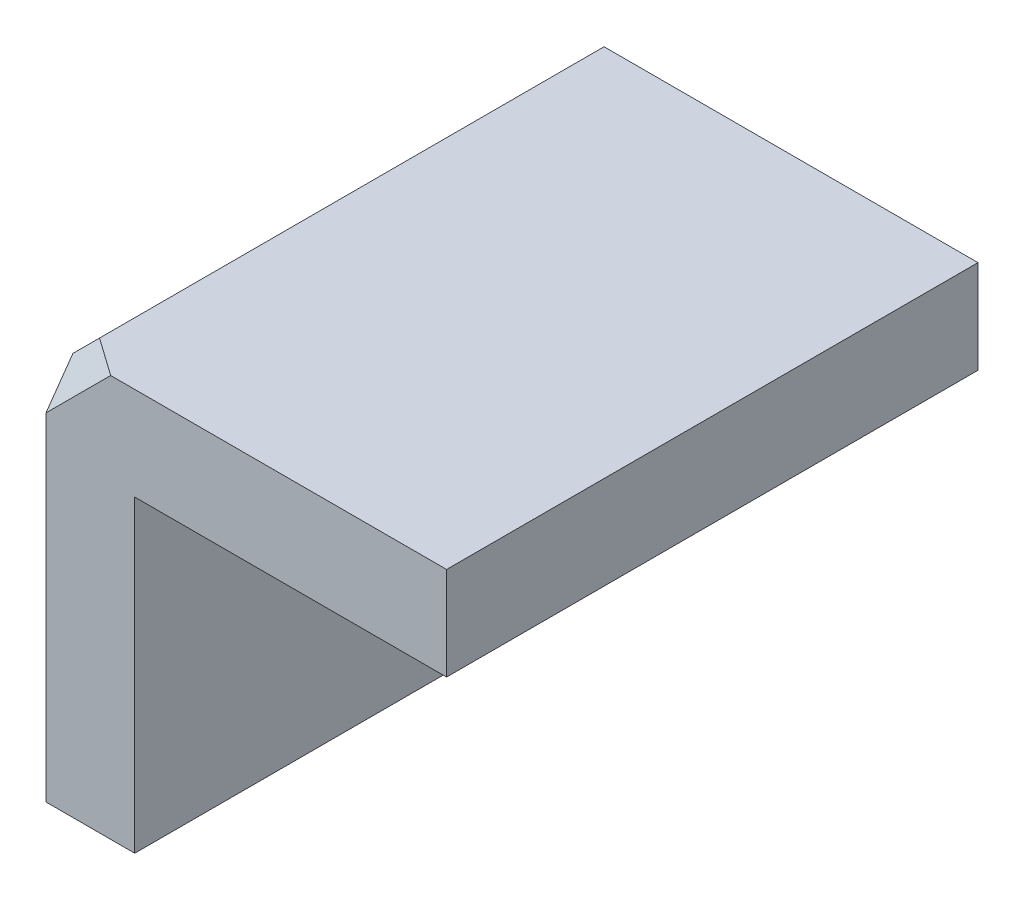
SolidWorks part; units mm, degrees
ref_plane "Front Plane" through (0, 0, 0) normal (0, 0, 1) x (1, 0, 0)
ref_plane "Top Plane" through (0, 0, 0) normal (0, 1, 0) x (1, 0, 0)
ref_plane "Right Plane" through (0, 0, 0) normal (1, 0, 0) x (0, 0, -1)
sketch "Sketch2" plane through (0, 0, 0) normal (0, 0, 1) x (1, 0, 0)
  line L0 (5.0138, 0) -> (75.3789, 0)
  line L1 (0, -5.0138) -> (0, -75.5918)
  line L2 (0, -75.5918) -> (16.6972, -75.5918)
  line L3 (16.6972, -75.5918) -> (16.6972, -17.5417)
  line L4 (16.6972, -17.5417) -> (75.3789, -17.5417)
  line L5 (75.3789, -17.5417) -> (75.3789, 0)
  line L6 (5.0138, 0) -> (0, -5.0138)
extrude "Boss-Extrude1" add sketch "Sketch2" against normal mid plane 100
ref_plane "Plane2" through (2.5069, -2.5069, 0) normal (-0.7071, 0.7071, 0) x (-0.7071, -0.7071, 0)
ref_plane "Plane3" through (-2.5069, -2.5069, 0) normal (0.7071, 0.7071, 0) x (0, 0, 1)
sketch "Sketch6" plane through (-2.5069, -2.5069, 0) normal (0.7071, 0.7071, 0) x (0, 0, 1)
  line L0 (44.9406, 3.5453) -> (50.1136, 8.7183)
  line L1 (-50, 3.5453) -> (50, 3.5453) construction
  line L2 (50.1136, 8.7183) -> (50.1136, 3.4944)
  line L3 (50.1136, 3.4944) -> (44.9406, 3.5453)
  point P1 (50.1136, 8.7183)
  dimension "D1" = 45
extrude "Cut-Extrude2" cut sketch "Sketch6" against normal through all both and the other way through all
